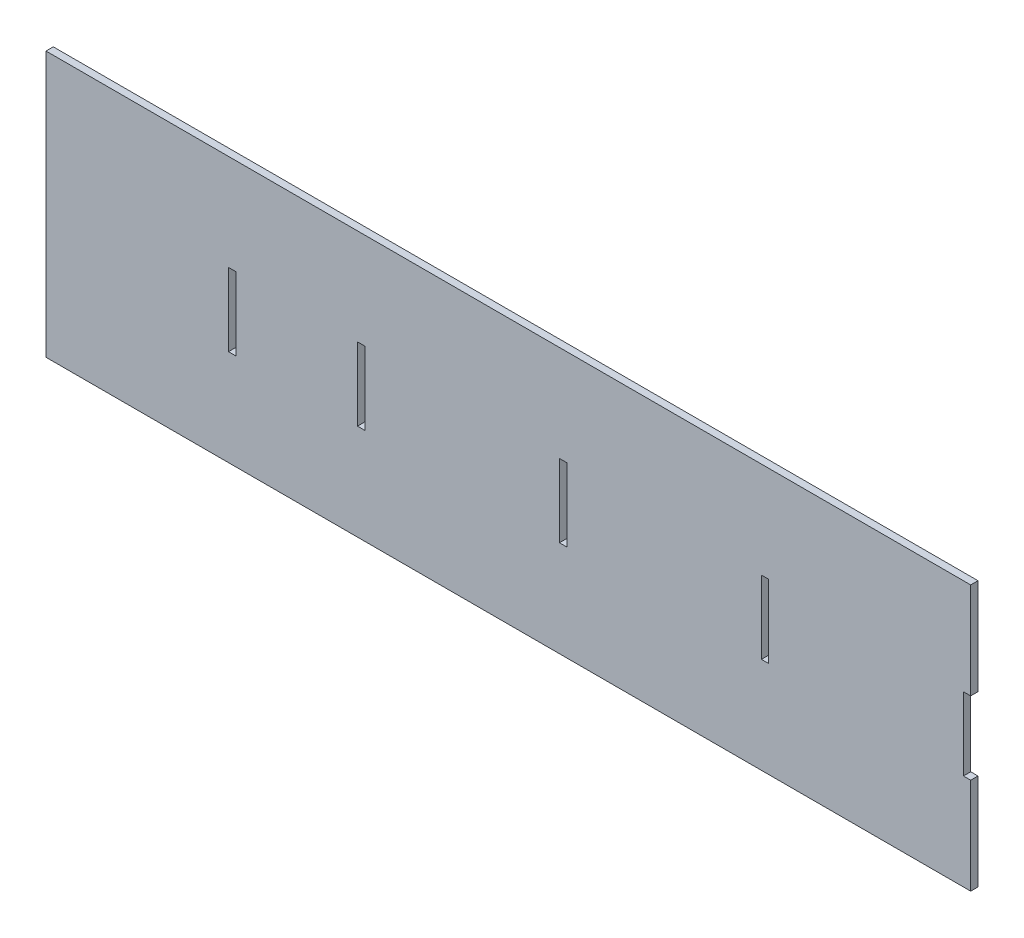
SolidWorks part; units mm, degrees
ref_plane "Front Plane" through (0, 0, 0) normal (0, 0, 1) x (1, 0, 0)
ref_plane "Top Plane" through (0, 0, 0) normal (0, 1, 0) x (1, 0, 0)
ref_plane "Right Plane" through (0, 0, 0) normal (1, 0, 0) x (0, 0, -1)
sketch "Sketch1" plane through (0, 0, 0) normal (0, 0, 1) x (1, 0, 0)
  line L1 (115, 109) -> (380, 109)
  line L3 (380, 0) -> (0, 0)
  line L5 (128, 69.5) -> (131, 69.5)
  line L6 (128, 69.5) -> (128, 39.5)
  line L7 (128, 39.5) -> (131, 39.5)
  line L8 (131, 69.5) -> (131, 39.5)
  line L14 (211, 69.5) -> (214, 69.5)
  line L15 (211, 69.5) -> (211, 39.5)
  line L16 (211, 39.5) -> (214, 39.5)
  line L17 (214, 69.5) -> (214, 39.5)
  line L18 (294, 69.5) -> (297, 69.5)
  line L19 (294, 69.5) -> (294, 39.5)
  line L20 (294, 39.5) -> (297, 39.5)
  line L21 (297, 69.5) -> (297, 39.5)
  line L22 (377, 69.5) -> (380, 69.5)
  line L23 (377, 69.5) -> (377, 39.5)
  line L24 (377, 39.5) -> (380, 39.5)
  line L55 (0, 0) -> (0, 109)
  line L56 (0, 109) -> (115, 109)
  line L57 (380, 69.5) -> (380, 109)
  line L58 (75, 69.5) -> (78, 69.5)
  line L59 (75, 69.5) -> (75, 39.5)
  line L60 (75, 39.5) -> (78, 39.5)
  line L61 (78, 69.5) -> (78, 39.5)
  line L62 (380, 39.5) -> (380, 0)
  line L63 (380, 54.5) -> (-683.0281, 54.5) construction
  point P12 (0, 0)
  point P53 (0, 0)
  point P54 (0, 0)
  dimension "D1" = 109
  dimension "D2" = 30
  dimension "D3" = 3
  dimension "D4" = 75
  dimension "D5" = 3
  dimension "D6" = 50
  dimension "D7" = 30
  dimension "D8" = 30
  dimension "D9" = 3
  dimension "D10" = 30
  dimension "D11" = 3
  dimension "D12" = 80
  dimension "D13" = 80
  dimension "D14" = 80
  dimension "D15" = 3
  dimension "D16" = 30
extrude "Boss-Extrude1" add sketch "Sketch1" along normal blind 3 contours L3 L1
